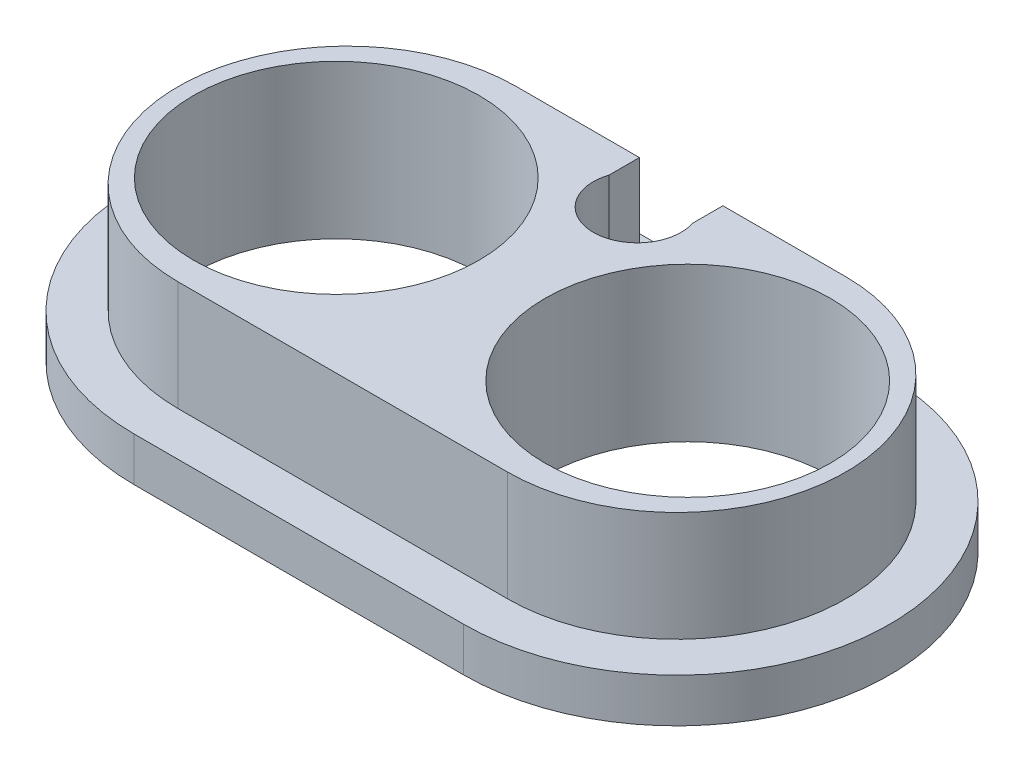
SolidWorks part; units mm, degrees
ref_plane "前基準面" through (0, 0, 0) normal (0, 0, 1) x (1, 0, 0)
ref_plane "上基準面" through (0, 0, 0) normal (0, 1, 0) x (1, 0, 0)
ref_plane "右基準面" through (0, 0, 0) normal (1, 0, 0) x (0, 0, -1)
sketch "草圖1" plane through (0, 0, 0) normal (0, 1, 0) x (1, 0, 0)
  line L0 (-7.5, 0) -> (7.5, 0) construction
  line L5 (-56.0698, 0) -> (56.0698, 0) construction
  line L6 (-7.5, 7.7) -> (7.5, 7.7)
  line L7 (-7.5, -7.7) -> (7.5, -7.7)
  arc A0 (-7.5, 7.7) -> (-7.5, -7.7) centre (-7.5, 0) ccw
  arc A1 (7.5, -7.7) -> (7.5, 7.7) centre (7.5, 0) ccw
  point P4 (0, 0)
  dimension "D2" = 15
  dimension "D1" = 15.4
sketch "草圖2" plane through (0, 0, 0) normal (0, 1, 0) x (1, 0, 0)
  line L0 (-7.5, 0) -> (7.5, 0) construction
  line L1 (-7.5, 9.7) -> (7.5, 9.7)
  line L2 (-7.5, -9.7) -> (7.5, -9.7)
  arc A0 (-7.5, 9.7) -> (-7.5, -9.7) centre (-7.5, 0) ccw
  arc A1 (7.5, -9.7) -> (7.5, 9.7) centre (7.5, 0) ccw
  point P4 (0, 0)
  dimension "D1" = 19.4
extrude "填料-伸長1" add sketch "草圖2" against normal blind 2
extrude "填料-伸長2" add sketch "草圖1" along normal blind 5 contours A0 L7 A1 L6
sketch "草圖3" plane through (0, -2, 0) normal (0, -1, 0) x (1, 0, 0)
  line L0 (3.85, 0) -> (-3.85, 0) construction
  line L1 (0, -3.85) -> (0, 3.85) construction
  line L3 (-7.5, -5.7) -> (7.5, -5.7)
  line L4 (-1.9, -6.3245) -> (-1.9, -9.7)
  line L5 (7.5, -9.7) -> (-7.5, -9.7) construction
  line L6 (-1.9, -9.7) -> (1.9, -9.7)
  line L7 (1.9, -9.7) -> (1.9, -6.3245)
  circle A1 centre (-8, 0) radius 6.5
  circle A2 centre (8, 0) radius 6.5
  arc A3 (-1.9, -6.3245) -> (1.9, -6.3245) centre (0, -5.7) cw
  point P17 (0, 0)
  point P18 (0, 0)
  line M4 (-7.5, -9.7) -> (7.5, -9.7)
  dimension "D1" = 13
  dimension "D2" = 8
  dimension "D3" = 13
  dimension "D4" = 2
  dimension "D5" = 8
  dimension "D6" = 3.8
  dimension "D7" = 4
extrude "除料-伸長1" cut sketch "草圖3" against normal up to next contours A1 | A2 | A3 L3 | A3 L4 L7 L3 M4
